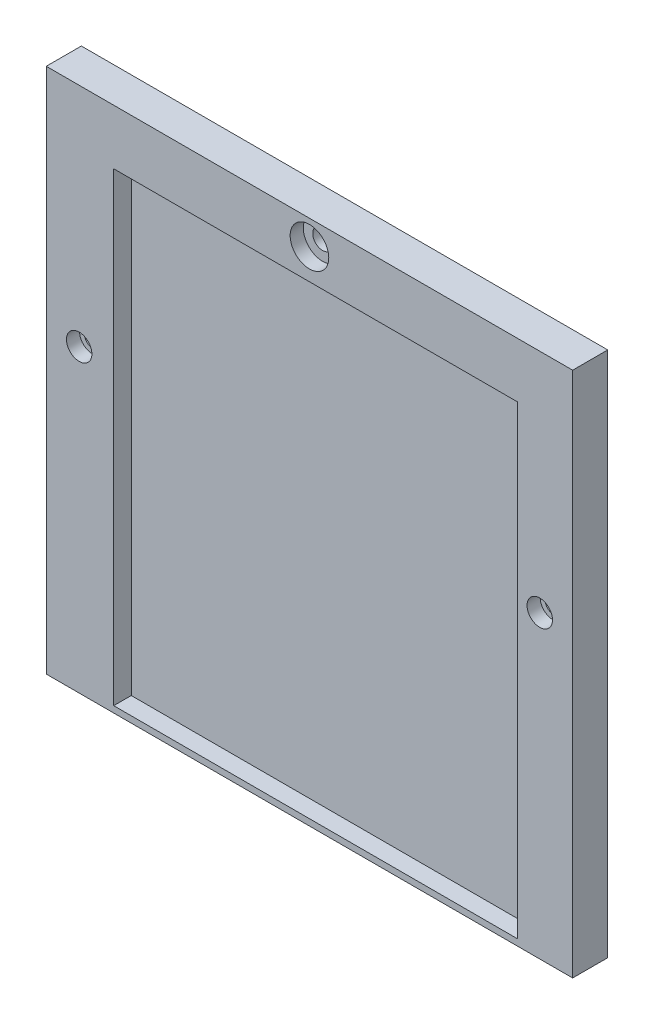
SolidWorks part; units mm, degrees
ref_plane "前视基准面" through (0, 0, 0) normal (0, 0, 1) x (1, 0, 0)
ref_plane "上视基准面" through (0, 0, 0) normal (0, 1, 0) x (1, 0, 0)
ref_plane "右视基准面" through (0, 0, 0) normal (1, 0, 0) x (0, 0, -1)
other "Configuration Table"
sketch "草图1" plane through (0, 0, 0) normal (0, 0, 1) x (1, 0, 0)
  line L1 (-55.1619, 83.0727) -> (64.8381, 83.0727)
  line L2 (-55.1619, 83.0727) -> (-55.1619, -36.9273)
  line L3 (-55.1619, -36.9273) -> (64.8381, -36.9273)
  line L4 (64.8381, 83.0727) -> (64.8381, -36.9273)
extrude "凸台-拉伸1" add sketch "草图1" along normal blind 8
sketch "草图3" plane through (0, 0, 8) normal (0, 0, 1) x (1, 0, 0)
  circle A0 centre (4.8381, 77.4543) radius 2.25
extrude "切除-拉伸1" cut sketch "草图3" against normal blind 8
sketch "草图4" plane through (0, 0, 8) normal (0, 0, 1) x (1, 0, 0)
  circle A0 centre (4.8381, 77.4543) radius 4.4
extrude "切除-拉伸2" cut sketch "草图4" against normal blind 3
sketch "草图5" plane through (0, 0, 8) normal (0, 0, 1) x (1, 0, 0)
  circle A0 centre (57.34, 31.45) radius 1.75
extrude "切除-拉伸3" cut sketch "草图5" against normal blind 8
sketch "草图6" plane through (0, 0, 8) normal (0, 0, 1) x (1, 0, 0)
  circle A0 centre (57.34, 31.45) radius 2.9
extrude "切除-拉伸4" cut sketch "草图6" against normal blind 3
sketch "草图7" plane through (0, 0, 8) normal (0, 0, 1) x (1, 0, 0)
  circle A1 centre (-47.66, 31.45) radius 1.75
extrude "切除-拉伸5" cut sketch "草图7" against normal blind 8
sketch "草图8" plane through (0, 0, 8) normal (0, 0, 1) x (1, 0, 0)
  circle A0 centre (-47.66, 31.45) radius 2.9
extrude "切除-拉伸6" cut sketch "草图8" against normal blind 3
sketch "草图9" plane through (0, 0, 8) normal (0, 0, 1) x (1, 0, 0)
  line L1 (-39.7844, 70.5265) -> (52.2156, 70.5265)
  line L2 (-39.7844, 70.5265) -> (-39.7844, -35.4735)
  line L3 (-39.7844, -35.4735) -> (52.2156, -35.4735)
  line L4 (52.2156, 70.5265) -> (52.2156, -35.4735)
  point P4 (-40.0549, 68.9545)
  point P5 (-40.0549, -27.0868)
  point P6 (-40.1902, 70.713)
  point P7 (-39.7844, -31.8212)
  point P8 (-39.7844, -35.4735)
extrude "切除-拉伸7" cut sketch "草图9" against normal blind 4 contours L2 L1 L4 L3
